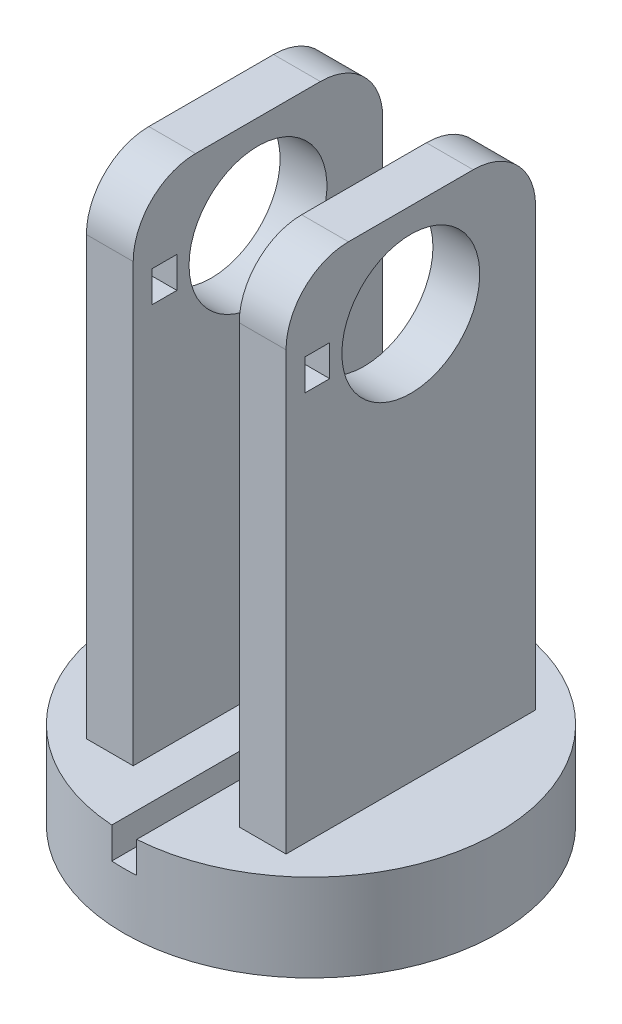
SolidWorks part; units mm, degrees
material "6061 Alloy"
ref_plane "Front Plane" through (0, 0, 0) normal (0, 0, 1) x (1, 0, 0)
ref_plane "Top Plane" through (0, 0, 0) normal (0, 1, 0) x (1, 0, 0)
ref_plane "Right Plane" through (0, 0, 0) normal (1, 0, 0) x (0, 0, -1)
sketch "Sketch1" plane through (0, 0, 0) normal (0, 1, 0) x (1, 0, 0)
  circle A0 centre (0, 0) radius 30
  dimension "D1" = 60
extrude "Boss-Extrude1" add sketch "Sketch1" along normal blind 14
sketch "Sketch2" plane through (0, 0, 0) normal (0, -1, 0) x (1, 0, 0)
  circle A0 centre (0, 0) radius 11.05
  dimension "D1" = 22.1
extrude "Cut-Extrude1" cut sketch "Sketch2" against normal blind 7
sketch "Sketch5" plane through (0, 14, 0) normal (0, 1, 0) x (1, 0, 0)
  line L0 (0, 0) -> (-8.5, 0) construction
  line L1 (0, 0) -> (8.5, 0) construction
  line L2 (-8.5, -20) -> (-8.5, 20)
  line L3 (-8.5, 20) -> (-16, 20)
  line L4 (-16, 20) -> (-16, -20)
  line L5 (-16, -20) -> (-8.5, -20)
  line L7 (16, -20) -> (16, 20)
  line L8 (16, 20) -> (8.5, 20)
  line L9 (8.5, 20) -> (8.5, -20)
  line L10 (8.5, -20) -> (16, -20)
  dimension "D1" = 8.5
  dimension "D2" = 8.5
  dimension "D3" = 7.5
  dimension "D4" = 20
  dimension "D5" = 20
  dimension "D6" = 0
  dimension "D7" = 7.5
  dimension "D8" = 20
  dimension "D9" = 20
extrude "Boss-Extrude2" add sketch "Sketch5" along normal blind 80
sketch "Sketch7" plane through (-16, 0, 0) normal (-1, 0, 0) x (0, 0, 1)
  line L0 (20, 94) -> (20, 14) construction
  line L1 (-20, 94) -> (20, 94) construction
  circle A0 centre (0, 79) radius 11.05
  dimension "D1" = 20
  dimension "D3" = 22.1
  dimension "D2" = 15
fillet "Fillet1" radius 10 4 edges at (-12.25, 94, -20) (12.25, 94, -20) (12.25, 94, 20) (-12.25, 94, 20)
extrude "Cut-Extrude3" cut sketch "Sketch7" against normal through all and the other way through all
sketch "Sketch8" plane through (0, 14, 0) normal (0, 1, 0) x (1, 0, 0)
  line L0 (0, 0) -> (2, 0) construction
  line L1 (0, 0) -> (-2, 0) construction
  line L2 (2, 29.9333) -> (2, -29.9333)
  line L3 (-2, 29.9333) -> (-2, -29.9333)
  circle A0 centre (0, 0) radius 30 construction
  arc A1 (-2, -29.9333) -> (2, -29.9333) centre (0, 0) ccw
  arc A2 (2, 29.9333) -> (-2, 29.9333) centre (0, 0) ccw
  dimension "D1" = 2
  dimension "D2" = 2
extrude "Cut-Extrude4" cut sketch "Sketch8" against normal blind 5
sketch "Sketch9" plane through (-16, 0, 0) normal (-1, 0, 0) x (0, 0, 1)
  line L0 (0, 79) -> (15, 79) construction
  line L2 (17, 76.5) -> (13, 76.5)
  line L3 (17, 76.5) -> (17, 81.5)
  line L4 (17, 81.5) -> (13, 81.5)
  line L5 (13, 76.5) -> (13, 81.5)
  line L6 (17, 76.5) -> (13, 81.5) construction
  line L7 (17, 81.5) -> (13, 76.5) construction
  dimension "D1" = 15
  dimension "D2" = 5
  dimension "D3" = 4
extrude "Cut-Extrude5" cut sketch "Sketch9" against normal up to surface (32 mm away) contours L2 L5 L4 L3 up to face at (16, 79, 11.05)
